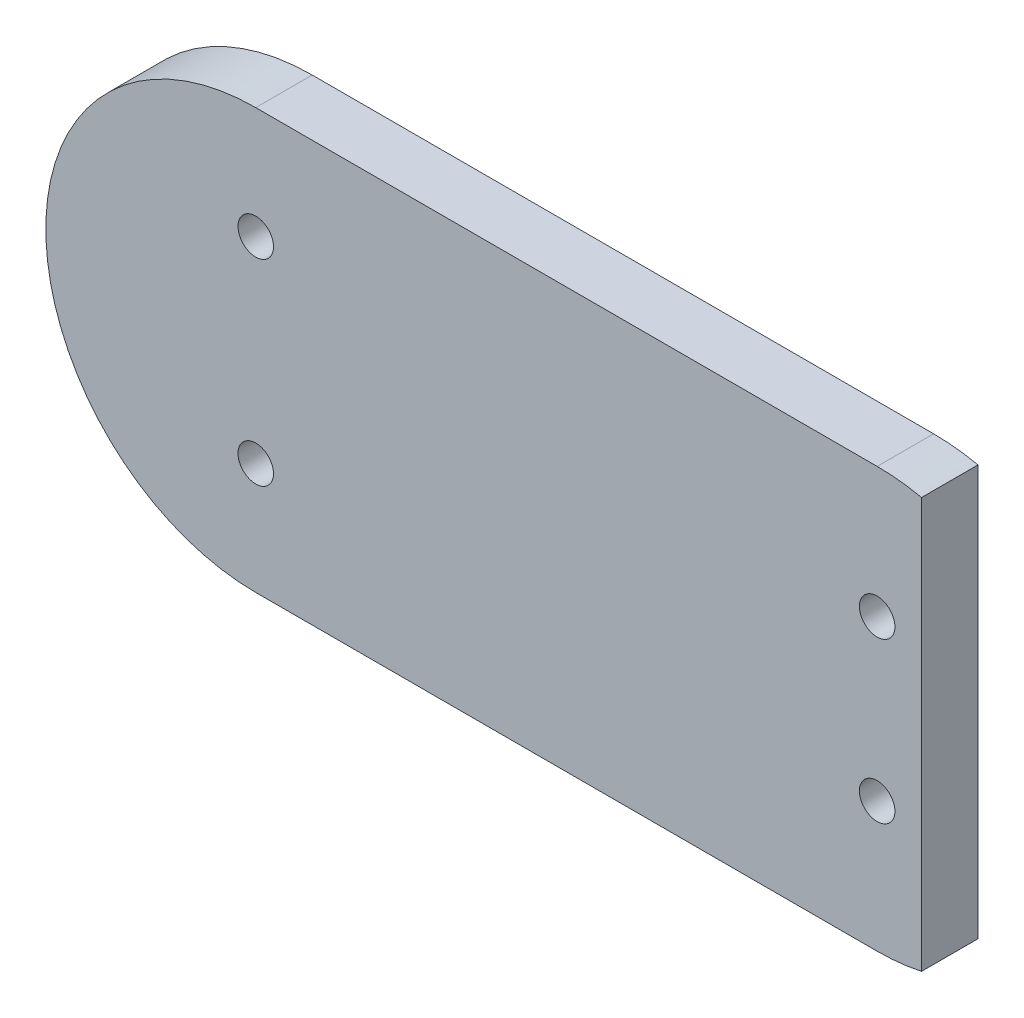
SolidWorks part; units mm, degrees
ref_plane "Front Plane" through (0, 0, 0) normal (0, 0, 1) x (1, 0, 0)
ref_plane "Top Plane" through (0, 0, 0) normal (0, 1, 0) x (1, 0, 0)
ref_plane "Right Plane" through (0, 0, 0) normal (1, 0, 0) x (0, 0, -1)
sketch "Sketch3" plane through (0, 0, 0) normal (0, 0, 1) x (1, 0, 0)
  line L0 (-17.5, 0) -> (17.5, 0) construction
  line L1 (-17.5, 11.825) -> (17.5, 11.825)
  line L2 (-17.5, -11.825) -> (17.5, -11.825)
  arc A0 (-17.5, 11.825) -> (-17.5, -11.825) centre (-17.5, 0) ccw
  arc A1 (17.5, -11.825) -> (17.5, 11.825) centre (17.5, 0) ccw
  point P2 (0, 0)
  dimension "D2" = 11.825
  dimension "D1" = 35
extrude "Boss-Extrude1" add sketch "Sketch3" along normal mid plane 3.18
sketch "Sketch4" plane through (0, 0, 1.59) normal (0, 0, 1) x (1, 0, 0)
  line L0 (-17.5, 11.825) -> (-17.5, -11.825) construction
  line L1 (0, 0) -> (-23.1703, 0) construction
  circle A0 centre (-17.5, 5.535) radius 1
  circle A1 centre (-17.5, -5.535) radius 1
  arc A2 (-17.5, 11.825) -> (-17.5, -11.825) centre (-17.5, 0) ccw construction
  dimension "D1" = 2
  dimension "D2" = 11.07
extrude "Cut-Extrude1" cut sketch "Sketch4" against normal blind 10
sketch "Sketch5" plane through (0, 0, 1.59) normal (0, 0, 1) x (1, 0, 0)
  line L0 (17.5, 4.5) -> (17.5, -4.5) construction
  line L1 (0, 0) -> (36.6378, 0) construction
  line L2 (0, 0) -> (0, -6.49) construction
  line L3 (20, 11.5577) -> (20, -11.5577)
  circle A0 centre (17.5, 4.5) radius 1
  circle A1 centre (17.5, -4.5) radius 1
  arc A2 (17.5, -11.825) -> (17.5, 11.825) centre (17.5, 0) ccw construction
  arc A3 (20, 11.5577) -> (20, -11.5577) centre (17.5, 0) cw
  dimension "D1" = 9
  dimension "D4" = 2
  dimension "D2" = 17.5
  dimension "D3" = 2.5
extrude "Cut-Extrude2" cut sketch "Sketch5" against normal through all
